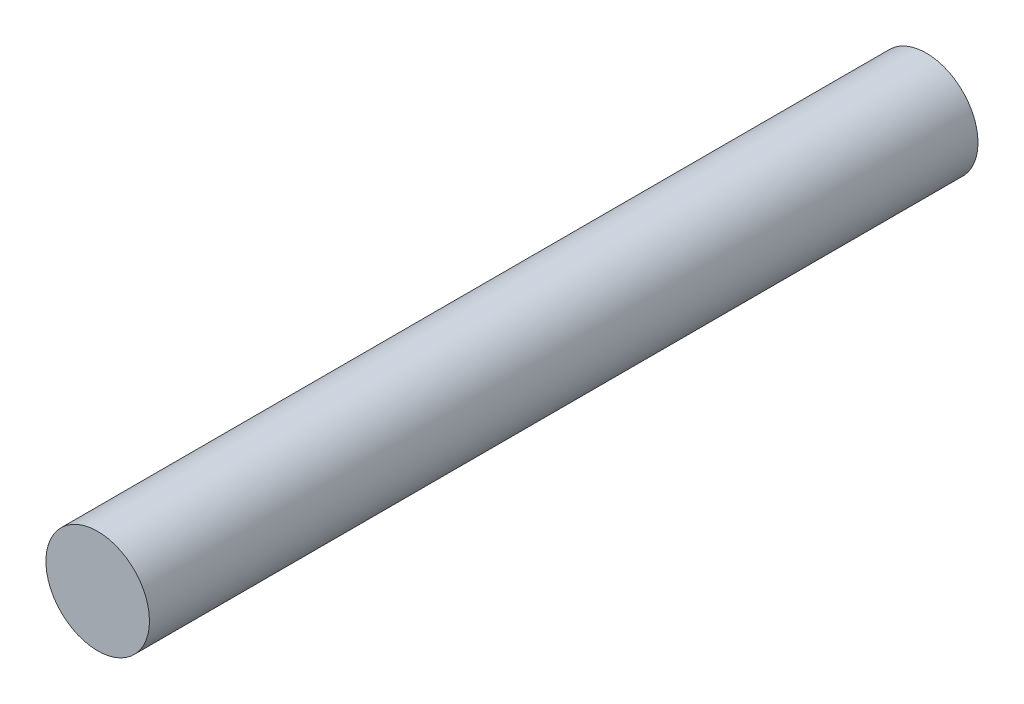
SolidWorks part; units mm, degrees
ref_plane "Front" through (0, 0, 0) normal (0, 0, 1) x (1, 0, 0)
ref_plane "Top" through (0, 0, 0) normal (0, 1, 0) x (1, 0, 0)
ref_plane "Right" through (0, 0, 0) normal (1, 0, 0) x (0, 0, -1)
sketch "Sketch1" plane through (0, 0, 0) normal (0, 0, 1) x (1, 0, 0)
  circle A0 centre (0, 0) radius 1.5875
  dimension "D1" = 3.175
extrude "Boss-Extrude1" add sketch "Sketch1" along normal blind 25.4
